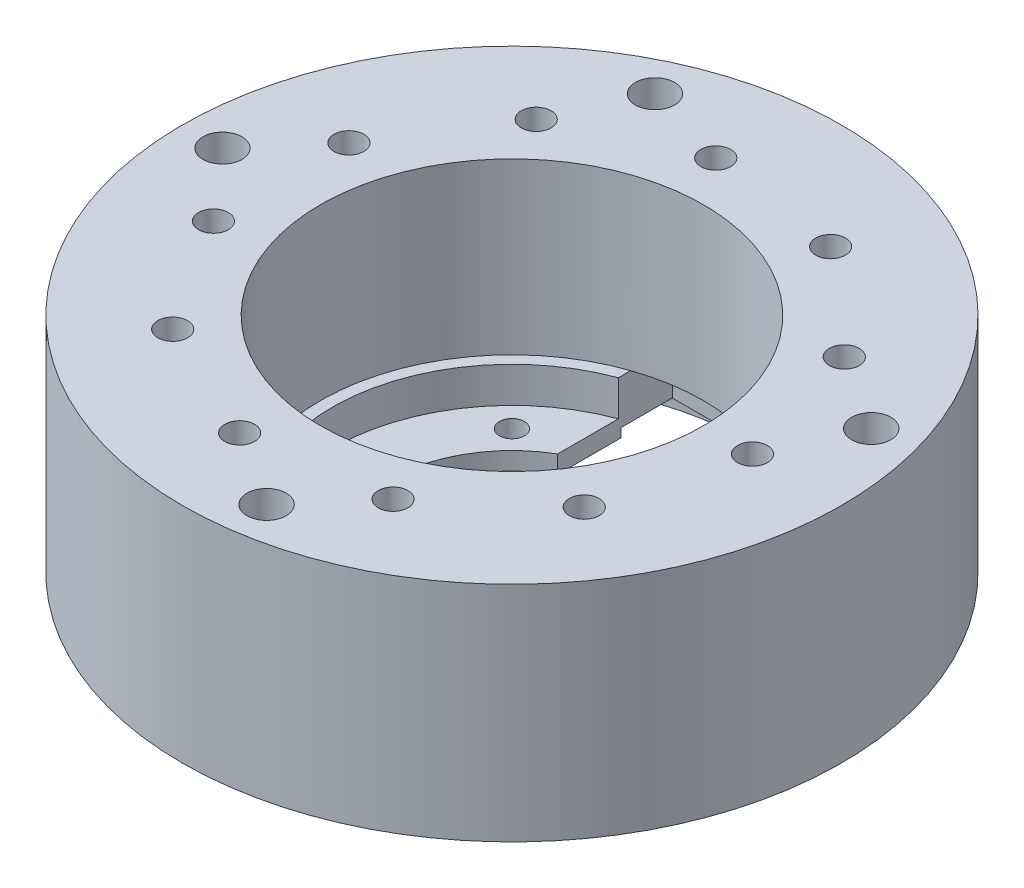
SolidWorks part; units mm, degrees
ref_plane "Front Plane" through (0, 0, 0) normal (0, 0, 1) x (1, 0, 0)
ref_plane "Top Plane" through (0, 0, 0) normal (0, 1, 0) x (1, 0, 0)
ref_plane "Right Plane" through (0, 0, 0) normal (1, 0, 0) x (0, 0, -1)
sketch "Sketch1" plane through (0, 0, 0) normal (0, 1, 0) x (1, 0, 0)
  circle A0 centre (0, 0) radius 37
  dimension "D1" = 74
extrude "Boss-Extrude1" add sketch "Sketch1" along normal blind 25.05
sketch "Sketch2" plane through (0, 25.05, 0) normal (0, 1, 0) x (1, 0, 0)
  circle A0 centre (0, 0) radius 21.5
  dimension "D1" = 43
extrude "Cut-Extrude1" cut sketch "Sketch2" against normal blind 19.05
sketch "Sketch3" plane through (0, 6, 0) normal (0, 1, 0) x (1, 0, 0)
  circle A0 centre (0, 0) radius 20.2
  dimension "D1" = 40.4
extrude "Cut-Extrude2" cut sketch "Sketch3" against normal blind 4
sketch "Sketch4" plane through (0, 2, 0) normal (0, 1, 0) x (1, 0, 0)
  circle A0 centre (0, 0) radius 14
  dimension "D1" = 28
extrude "Cut-Extrude3" cut sketch "Sketch4" against normal through all
sketch "Sketch5" plane through (0, 0, 0) normal (0, 1, 0) x (1, 0, 0)
  line L0 (0, -13.7775) -> (0, 13.7775) construction
  line L1 (-7, 11) -> (7, 11)
  line L2 (-7, 11) -> (-7, 25)
  line L3 (-7, 25) -> (7, 25)
  line L4 (7, 11) -> (7, 25)
  line L5 (-7, 11) -> (7, 25) construction
  line L6 (-7, 25) -> (7, 11) construction
  line L7 (-13.7775, 0) -> (13.7775, 0) construction
  point P0 (0, 18)
  dimension "D1" = 14
  dimension "D2" = 11
  dimension "D3" = 25
extrude "Cut-Extrude4" cut sketch "Sketch5" along normal blind 6
sketch "Sketch6" plane through (0, 0, 0) normal (0, 1, 0) x (1, 0, 0)
  line L0 (-13.7775, 0) -> (13.7775, 0) construction
  line L1 (0, -13.7775) -> (0, 13.7775) construction
  circle A0 centre (12.021, 12.021) radius 1.4
  circle A1 centre (12.021, -12.021) radius 1.4
  circle A2 centre (-12.021, -12.021) radius 1.4
  circle A3 centre (-12.021, 12.021) radius 1.4
  point P15 (0, 0)
  dimension "D1" = 2.8
  dimension "D2" = 12.021
  dimension "D3" = 12.021
  dimension "D4" = 4
extrude "Cut-Extrude5" cut sketch "Sketch6" along normal through all
sketch "Sketch7" plane through (0, 25.05, 0) normal (0, 1, 0) x (1, 0, 0)
  line L0 (-13.7775, 0) -> (13.7775, 0) construction
  line L1 (0, -13.7775) -> (0, 13.7775) construction
  circle A0 centre (27, 0) radius 1.675
  circle A1 centre (22.7138, -14.5973) radius 1.675
  circle A2 centre (11.2162, -24.5601) radius 1.675
  circle A3 centre (-3.8425, -26.7252) radius 1.675
  circle A4 centre (-17.6812, -20.4052) radius 1.675
  circle A5 centre (-25.9063, -7.6068) radius 1.675
  circle A6 centre (-25.9063, 7.6068) radius 1.675
  circle A7 centre (-17.6812, 20.4052) radius 1.675
  circle A8 centre (-3.8425, 26.7252) radius 1.675
  circle A9 centre (11.2162, 24.5601) radius 1.675
  circle A10 centre (22.7138, 14.5973) radius 1.675
  point P28 (0, 0)
  dimension "D1" = 3.35
  dimension "D2" = 27
  dimension "D3" = 11
extrude "Cut-Extrude6" cut sketch "Sketch7" against normal blind 4.75
sketch "Sketch8" plane through (0, 25.05, 0) normal (0, 1, 0) x (1, 0, 0)
  line L0 (0, 0) -> (43.2403, 0) construction
  line L1 (-13.7775, 0) -> (13.7775, 0) construction
  line L2 (0, 0) -> (44.2582, 12.9923) construction
  line L3 (0, 0) -> (-20.2523, 44.3371) construction
  line L4 (0, 0) -> (-46.5124, 0) construction
  line L5 (0, 0) -> (7.8044, -54.2928) construction
  circle A0 centre (31.1841, 9.1543) radius 2.2
  circle A1 centre (-13.5033, 29.562) radius 2.2
  circle A2 centre (-32.5, 0) radius 2.2
  circle A4 centre (4.6242, -32.1693) radius 2.2
  dimension "D5" = 4.4
  dimension "D7" = 4.4
  dimension "D9" = 4.4
  dimension "D11" = 4.4
  dimension "D1" = 16.36
  dimension "D2" = 114.55
  dimension "D3" = 180
  dimension "D4" = 278.18
  dimension "D6" = 32.5
  dimension "D8" = 32.5
  dimension "D10" = 32.5
  dimension "D12" = 32.5
extrude "Cut-Extrude7" cut sketch "Sketch8" against normal blind 5.5
sketch "Sketch9" plane through (0, 0, 0) normal (0, 1, 0) x (1, 0, 0)
  circle A0 centre (0, 0) radius 20.5
  circle A1 centre (0, 0) radius 26
  dimension "D1" = 52
  dimension "D2" = 41
extrude "Cut-Extrude8" cut sketch "Sketch9" along normal blind 1
equation "\"pin_circle_R\" = 27"
equation "\"ecc\" = 1.5"
equation "\"n_pins\" = 11"
equation "\"pin_d\" = 3"
equation "\"out_pin_R\" = 18.5"
equation "\"disc_clr\" = 0.1"
equation "\"seat_6803\" = 26.1"
equation "\"seat_6806\" = 42.1"
equation "\"disc_t\" = 5"
equation "\"out_hole_clr\" = 0.5"
equation "\"boss_17\" = 17.13"
equation "\"rotor_bolt_R\" = 10"
equation "\"m25_clr\" = 2.8"
equation "\"m25_head\" = 5"
equation "\"insert_hole\" = 4.4"
equation "\"csk\" = 0.6"
equation "\"peg_d\" = 3.0"
equation "\"plug_d\" = 8.6"
equation "\"peg_clr\" = 0.3"
equation "\"m3_clr\" = 3.4"
equation "\"m3_head\" = 6.2"
equation "\"pin_press\" = 3.2"
equation "\"pin_slip\" = 3.35"
equation "\"hub_30\" = 30.18"
equation "\"hub_short\" = 0.2"
equation "\"m3_tap\" = 2.8"
equation "\"rear_plate_t\" = 2"
equation "\"motor_ring\" = 40.4"
equation "\"D1@Boss-Extrude1\"=\"rear_plate_t\" + 17.8 + 5.25"
equation "\"D1@Sketch6\"=\"m25_clr\""
equation "\"D1@Sketch7\"=\"pin_slip\""
equation "\"D2@Sketch7\"=\"pin_circle_R\""
equation "\"D5@Sketch8\"=\"insert_hole\""
equation "\"D7@Sketch8\"=\"insert_hole\""
equation "\"D9@Sketch8\"=\"insert_hole\""
equation "\"D11@Sketch8\"=\"insert_hole\""
equation "\"plug_shaft_d\" = 8.8"
